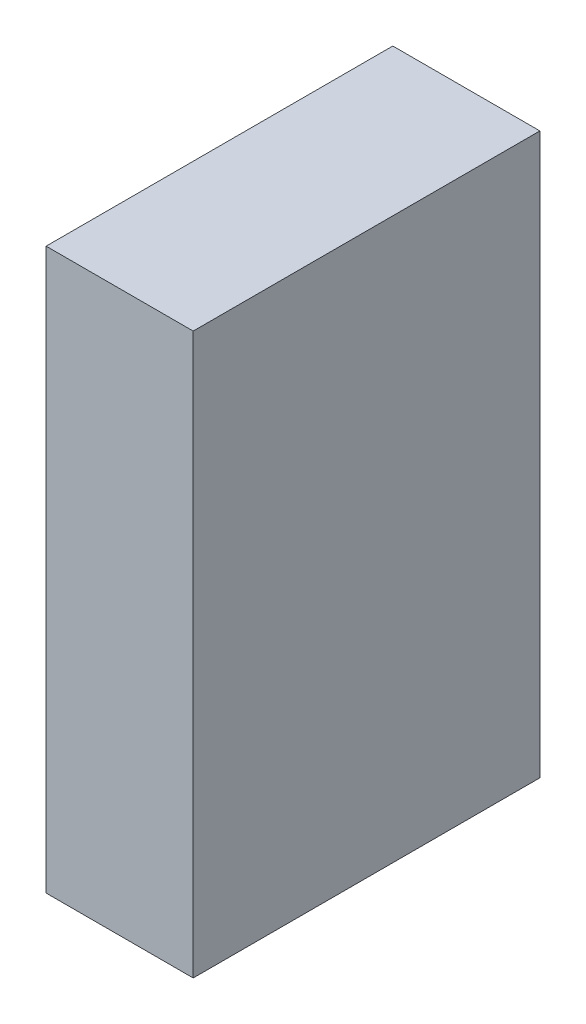
SolidWorks part; units mm, degrees
ref_plane "Front Plane" through (0, 0, 0) normal (0, 0, 1) x (1, 0, 0)
ref_plane "Top Plane" through (0, 0, 0) normal (0, 1, 0) x (1, 0, 0)
ref_plane "Right Plane" through (0, 0, 0) normal (1, 0, 0) x (0, 0, -1)
sketch "Sketch1" plane through (0, 0, 0) normal (0, 0, 1) x (1, 0, 0)
  line L1 (-21, 80) -> (21, 80)
  line L2 (-21, 80) -> (-21, -80)
  line L3 (-21, -80) -> (21, -80)
  line L4 (21, 80) -> (21, -80)
  line L5 (-21, 80) -> (21, -80) construction
  line L6 (-21, -80) -> (21, 80) construction
  point P0 (0, 0)
  dimension "D1" = 42
  dimension "D2" = 160
extrude "Boss-Extrude1" add sketch "Sketch1" along normal blind 99
